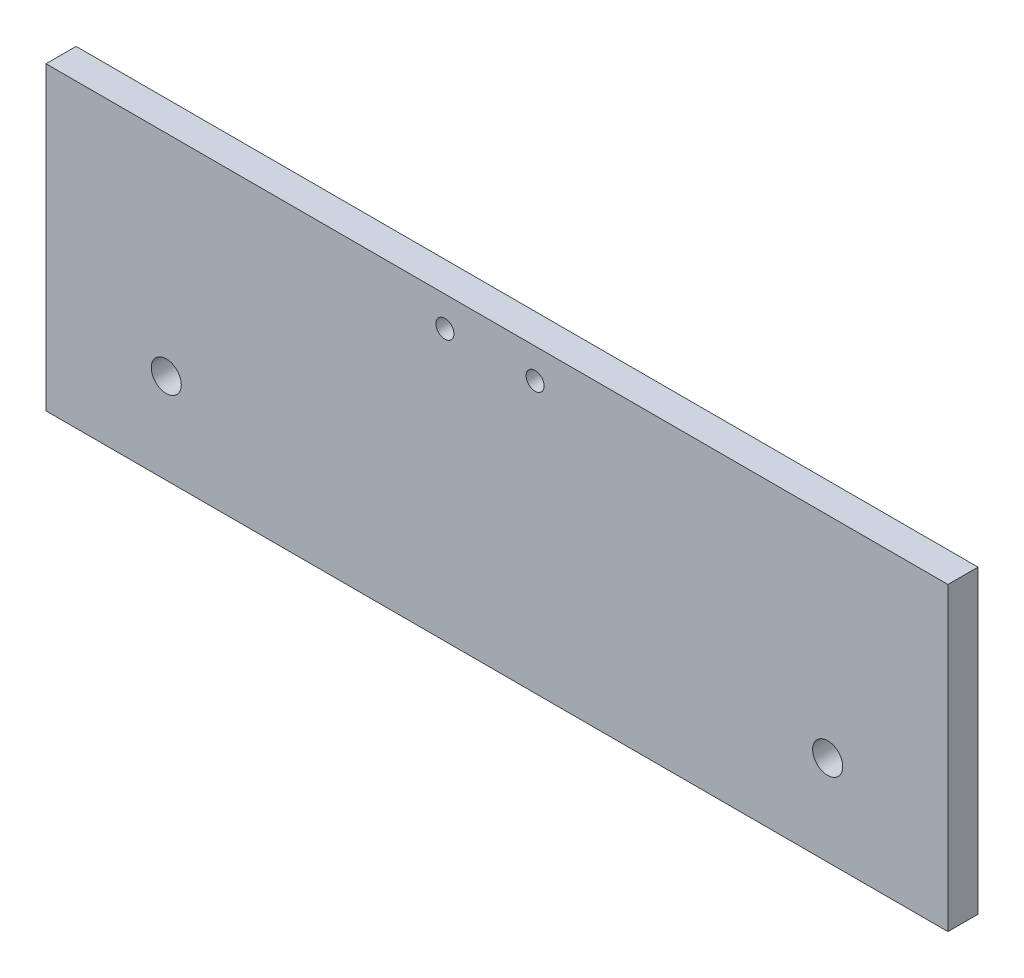
SolidWorks part; units mm, degrees
ref_plane "Plan de face" through (0, 0, 0) normal (0, 0, 1) x (1, 0, 0)
ref_plane "Plan de dessus" through (0, 0, 0) normal (0, 1, 0) x (1, 0, 0)
ref_plane "Plan de droite" through (0, 0, 0) normal (1, 0, 0) x (0, 0, -1)
sketch "Esquisse1" plane through (0, 0, 0) normal (0, 0, 1) x (1, 0, 0)
  line L0 (-113.4618, 0) -> (186.5382, 0)
  line L1 (186.5382, 0) -> (186.5382, 100)
  line L2 (186.5382, 100) -> (-113.4618, 100)
  line L3 (-113.4618, 100) -> (-113.4618, 0)
extrude "Boss.-Extru.1" add sketch "Esquisse1" along normal blind 10
sketch "Esquisse2" plane through (0, 0, 10) normal (0, 0, 1) x (1, 0, 0)
  circle A0 centre (49.2242, 90) radius 3
  circle A1 centre (19.2242, 90) radius 3
extrude "Enlèv. mat.-Extru.1" cut sketch "Esquisse2" against normal through all
sketch "Esquisse3" plane through (0, 0, 10) normal (0, 0, 1) x (1, 0, 0)
  line L0 (-113.4618, 0) -> (186.5382, 0) construction
  line L2 (-113.4618, 100) -> (-113.4618, 0) construction
  line L3 (186.5382, 0) -> (186.5382, 100) construction
  circle A0 centre (-73.4618, 30) radius 5
  circle A1 centre (146.5382, 30) radius 5
  dimension "D1" = 10
  dimension "D2" = 30
  dimension "D3" = 40
  dimension "D4" = 40
  dimension "D5" = 30
extrude "Enlèv. mat.-Extru.2" cut sketch "Esquisse3" against normal through all
